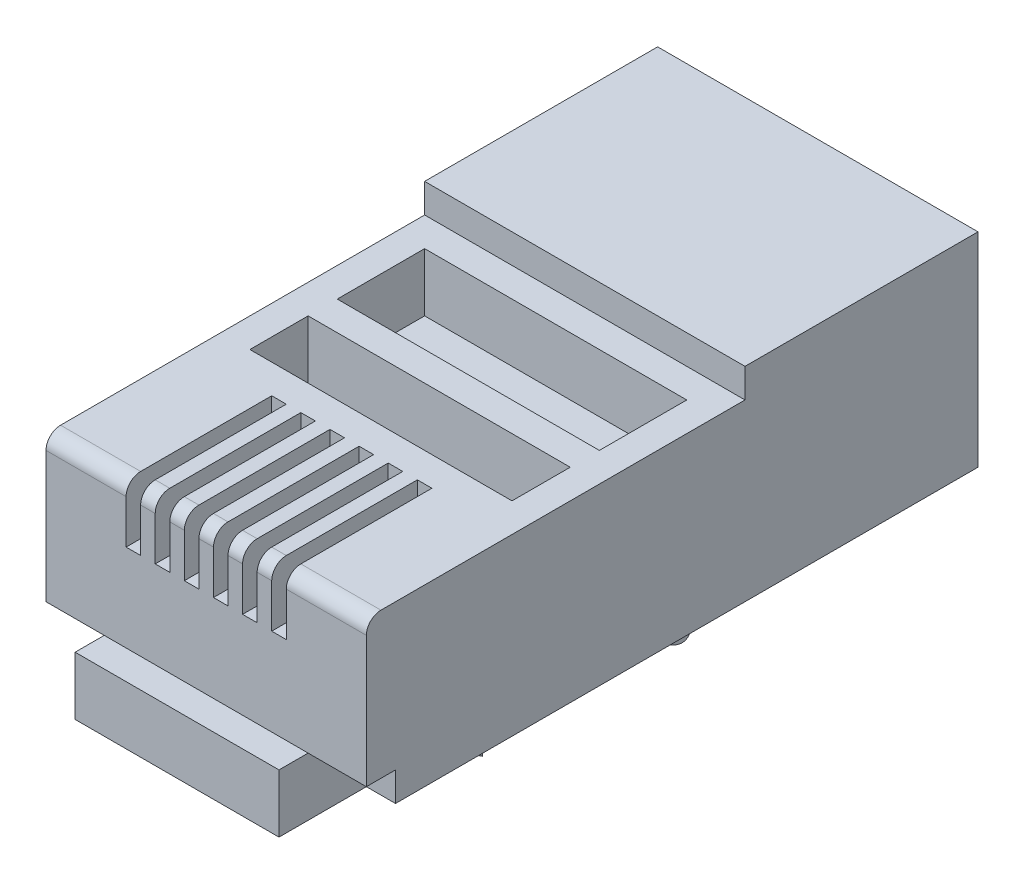
SolidWorks part; units mm, degrees
ref_plane "Ön Düzlem" through (0, 0, 0) normal (0, 0, 1) x (1, 0, 0)
ref_plane "Üst Düzlem" through (0, 0, 0) normal (0, 1, 0) x (1, 0, 0)
ref_plane "Sağ Düzlem" through (0, 0, 0) normal (1, 0, 0) x (0, 0, -1)
sketch "Sketch1" plane through (0, 0, 0) normal (0, 0, 1) x (1, 0, 0)
  line L0 (-58.5749, 4) -> (-58.5749, 6)
  line L1 (-61.8249, 6) -> (-59.0749, 6)
  line L2 (-61.8249, 6) -> (-61.8249, 0)
  line L3 (-61.8249, 0) -> (-50.8249, 0)
  line L4 (-50.8249, 6) -> (-50.8249, 0)
  line L5 (-58.5749, 6) -> (-58.0749, 6)
  line L6 (-59.0749, 6) -> (-59.0749, 4)
  line L7 (-59.0749, 4) -> (-58.5749, 4)
  line L8 (-53.5749, 6) -> (-53.5749, 4)
  line L9 (-58.0749, 4) -> (-58.0749, 6)
  line L10 (-57.5749, 4) -> (-57.5749, 6)
  line L11 (-57.0749, 6) -> (-57.0749, 4)
  line L12 (-56.5749, 6) -> (-56.5749, 4)
  line L13 (-56.0749, 6) -> (-56.0749, 4)
  line L14 (-58.5749, 6) -> (-58.0749, 6)
  line L15 (-57.5749, 6) -> (-57.0749, 6)
  line L16 (-57.5749, 6) -> (-57.0749, 6)
  line L17 (-56.5749, 6) -> (-56.0749, 6)
  line L18 (-56.5749, 6) -> (-56.0749, 6)
  line L19 (-58.0749, 4) -> (-57.5749, 4)
  line L20 (-57.0749, 4) -> (-56.5749, 4)
  line L21 (-56.0749, 4) -> (-55.5749, 4)
  line L22 (-55.5749, 4) -> (-55.5749, 6)
  line L23 (-55.0749, 6) -> (-55.0749, 4)
  line L24 (-55.0749, 4) -> (-54.5749, 4)
  line L25 (-54.5749, 6) -> (-54.5749, 4)
  line L26 (-55.5749, 6) -> (-55.0749, 6)
  line L27 (-55.5749, 6) -> (-55.0749, 6)
  line L28 (-54.5749, 6) -> (-54.0749, 6)
  line L29 (-54.5749, 6) -> (-54.0749, 6)
  line L30 (-54.0749, 4) -> (-54.0749, 6)
  line L31 (-54.0749, 4) -> (-53.5749, 4)
  line L32 (-53.5749, 6) -> (-50.8249, 6)
  dimension "D1" = 6
  dimension "D2" = 11
  dimension "D3" = 2.75
  dimension "D4" = 0.5
  dimension "D5" = 0.5
  dimension "D6" = 0.5
  dimension "D7" = 0.5
  dimension "D8" = 0.5
  dimension "D9" = 0.5
  dimension "D10" = 0.5
  dimension "D11" = 0.5
  dimension "D12" = 0.5
  dimension "D13" = 0.5
  dimension "D14" = 0.5
  dimension "D15" = 2
extrude "Boss-Extrude1" add sketch "Sketch1" against normal blind 5 contours L32 L8 L31 L30 L28 L25 L24 L23 L26 L22 L21 L13 L17 L12 L20 L11 L15 L10 L19 L9 L5 L0 L7 L6 L1 L2 L3 L4
sketch "Sketch2" plane through (0, 0, -5) normal (0, 0, -1) x (-1, 0, 0)
  line L1 (50.8249, 6) -> (61.8249, 6)
  line L2 (50.8249, 6) -> (50.8249, 0)
  line L3 (50.8249, 0) -> (61.8249, 0)
  line L4 (61.8249, 6) -> (61.8249, 0)
extrude "Boss-Extrude2" add sketch "Sketch2" along normal blind 8
sketch "Sketch3" plane through (0, 6, 0) normal (0, 1, 0) x (1, 0, 0)
  line L0 (-56.0749, 5) -> (-55.5749, 5) construction
  line L1 (-60.8249, 6) -> (-51.8249, 6)
  line L2 (-60.8249, 6) -> (-60.8249, 8)
  line L3 (-60.8249, 8) -> (-51.8249, 8)
  line L4 (-51.8249, 6) -> (-51.8249, 8)
  line L5 (-50.8249, 13) -> (-50.8249, 0) construction
  line L6 (-61.8249, 13) -> (-61.8249, 0) construction
  dimension "D1" = 1
  dimension "D2" = 1
  dimension "D3" = 1
  dimension "D4" = 2
extrude "Cut-Extrude1" cut sketch "Sketch3" against normal blind 2
sketch "Sketch5" plane through (0, 6, 0) normal (0, 1, 0) x (1, 0, 0)
  line L0 (-51.8249, 8) -> (-60.8249, 8) construction
  line L1 (-60.8249, 9) -> (-51.8249, 9)
  line L2 (-60.8249, 9) -> (-60.8249, 12)
  line L3 (-60.8249, 12) -> (-51.8249, 12)
  line L4 (-51.8249, 12) -> (-51.8249, 9)
  line L5 (-61.8249, 13) -> (-61.8249, 0) construction
  line L8 (-50.8249, 13) -> (-50.8249, 0) construction
  line L9 (-61.8249, 13) -> (-50.8249, 13) construction
  dimension "D1" = 1
  dimension "D2" = 1
  dimension "D3" = 1
  dimension "D4" = 1
extrude "Cut-Extrude2" cut sketch "Sketch5" against normal blind 2
sketch "Sketch7" plane through (0, 0, -13) normal (0, 0, -1) x (-1, 0, 0)
  line L1 (50.8249, 0) -> (61.8249, 0)
  line L2 (50.8249, 0) -> (50.8249, 7)
  line L3 (50.8249, 7) -> (61.8249, 7)
  line L4 (61.8249, 0) -> (61.8249, 7)
  line L5 (61.8249, 6) -> (50.8249, 6) construction
  dimension "D1" = 1
extrude "Boss-Extrude3" add sketch "Sketch7" along normal blind 8
sketch "Sketch8" plane through (0, 0, 0) normal (0, 0, 1) x (1, 0, 0)
  line L0 (-61.8249, 6) -> (-61.8249, 0) construction
  line L1 (-59.8249, 1) -> (-52.8249, 1)
  line L2 (-59.8249, 1) -> (-59.8249, -1)
  line L3 (-59.8249, -1) -> (-52.8249, -1)
  line L4 (-52.8249, 1) -> (-52.8249, -1)
  line L5 (-50.8249, 6) -> (-50.8249, 0) construction
  line L6 (-61.8249, 0) -> (-50.8249, 0) construction
  dimension "D1" = 2
  dimension "D2" = 2
  dimension "D3" = 1
  dimension "D4" = 1
extrude "Boss-Extrude4" add sketch "Sketch8" along normal blind 1
sketch "Sketch9" plane through (0, 0, 0) normal (0, 0, 1) x (1, 0, 0)
  line L0 (-52.8249, 0) -> (-52.8249, 1) construction
  line L1 (-59.8249, 1) -> (-61.8249, 1)
  line L2 (-59.8249, 1) -> (-59.8249, 0)
  line L3 (-59.8249, 0) -> (-61.8249, 0)
  line L4 (-61.8249, 1) -> (-61.8249, 0)
  line L5 (-50.8249, 0) -> (-52.8249, 0)
  line L6 (-50.8249, 0) -> (-50.8249, 1)
  line L7 (-50.8249, 1) -> (-52.8249, 1)
  line L8 (-52.8249, 0) -> (-52.8249, 1)
extrude "Cut-Extrude3" cut sketch "Sketch9" against normal blind 1
sketch "Sketch10" plane through (0, 0, 0) normal (0, -1, 0) x (1, 0, 0)
  line L1 (-59.8249, 0) -> (-52.8249, 0)
  line L2 (-59.8249, 0) -> (-59.8249, -3)
  line L3 (-59.8249, -3) -> (-52.8249, -3)
  line L4 (-52.8249, 0) -> (-52.8249, -3)
  dimension "D1" = 3
extrude "Boss-Extrude5" add sketch "Sketch10" along normal blind 1
sketch "Sketch12" plane through (-52.8249, 0, 0) normal (1, 0, 0) x (0, 0, -1)
  line L0 (3, 0) -> (5.9924, -0.4844)
  line L1 (5.9924, -0.4844) -> (5.9924, -2.0955)
  line L2 (5.9924, -2.0955) -> (4.8965, -1.3396)
  line L3 (4.8965, -1.3396) -> (3, -1)
  line L4 (3, -1) -> (3, 0)
extrude "Boss-Extrude6" add sketch "Sketch12" against normal blind 7
ref_plane "Plane2" through (-53.8249, 0, 0) normal (1, 0, 0) x (0, 0, -1)
sketch "Sketch13" plane through (-53.8249, 0, 0) normal (1, 0, 0) x (0, 0, -1)
  line L0 (14.149, -2.4619) -> (14.149, -2.8398)
  line L1 (5.9924, -2.0955) -> (5.9924, -0.4844)
  arc A0 (14.149, -2.4619) -> (13.9439, -2.1773) centre (13.849, -2.4619) ccw
  arc A1 (13.8795, -3.1383) -> (14.149, -2.8398) centre (13.849, -2.8398) ccw
  spline S0 degree 3 poles (5.9924, -0.4844) (8.7077, -0.7502) (11.3599, -1.3149) (13.9439, -2.1773) knots 0 0 0 0 0.957735 0.957735 0.957735 0.957735
  spline S1 degree 3 poles (5.9924, -2.0955) (8.2912, -2.4166) (10.9326, -1.9089) (13.4495, -2.9904) (13.6965, -3.157) (13.8795, -3.1383) knots 0 0 0 0 0.841667 0.882834 0.948247 0.948247 0.948247 0.948247
  dimension "D1" = 0.3
  dimension "D2" = 0.3
extrude "Boss-Extrude7" add sketch "Sketch13" against normal blind 5
sketch "Sketch14" plane through (0, 4, 0) normal (0, 1, 0) x (1, 0, 0)
  line L0 (-53.5749, 5) -> (-53.5749, 0) construction
  line L1 (-53.5749, 1.5) -> (-54.0749, 1.5)
  line L2 (-53.5749, 1.5) -> (-53.5749, 3.5)
  line L3 (-53.5749, 3.5) -> (-54.0749, 3.5)
  line L4 (-54.0749, 1.5) -> (-54.0749, 3.5)
  line L5 (-54.0749, 5) -> (-54.0749, 0) construction
  line L6 (-54.0749, 0) -> (-53.5749, 0) construction
  line L8 (-54.5749, 1.5) -> (-55.0749, 1.5)
  line L9 (-54.5749, 1.5) -> (-54.5749, 3.5)
  line L10 (-54.5749, 3.5) -> (-55.0749, 3.5)
  line L11 (-55.0749, 1.5) -> (-55.0749, 3.5)
  line L12 (-55.5749, 1.5) -> (-56.0749, 1.5)
  line L13 (-55.5749, 1.5) -> (-55.5749, 3.5)
  line L14 (-55.5749, 3.5) -> (-56.0749, 3.5)
  line L15 (-56.0749, 1.5) -> (-56.0749, 3.5)
  line L16 (-56.5749, 1.5) -> (-57.0749, 1.5)
  line L17 (-56.5749, 1.5) -> (-56.5749, 3.5)
  line L18 (-56.5749, 3.5) -> (-57.0749, 3.5)
  line L19 (-57.0749, 1.5) -> (-57.0749, 3.5)
  line L20 (-57.5749, 1.5) -> (-58.0749, 1.5)
  line L21 (-57.5749, 1.5) -> (-57.5749, 3.5)
  line L22 (-57.5749, 3.5) -> (-58.0749, 3.5)
  line L23 (-58.0749, 1.5) -> (-58.0749, 3.5)
  line L24 (-58.5749, 1.5) -> (-59.0749, 1.5)
  line L25 (-58.5749, 1.5) -> (-58.5749, 3.5)
  line L26 (-58.5749, 3.5) -> (-59.0749, 3.5)
  line L27 (-59.0749, 1.5) -> (-59.0749, 3.5)
  point P8 (-53.8249, 0)
  dimension "D1" = 1.5
  dimension "D2" = 2
  dimension "D3" = 6
extrude "Cut-Extrude4" cut sketch "Sketch14" against normal blind 1
sketch "Sketch15" plane through (0, 0, -21) normal (0, 0, -1) x (-1, 0, 0)
  line L0 (61.8249, 7) -> (50.8249, 7) construction
  line L1 (52.8249, 5) -> (59.8249, 5)
  line L2 (52.8249, 5) -> (52.8249, 2)
  line L3 (52.8249, 2) -> (59.8249, 2)
  line L4 (59.8249, 5) -> (59.8249, 2)
  line L5 (50.8249, 7) -> (50.8249, 0) construction
  line L6 (61.8249, 0) -> (61.8249, 7) construction
  line L7 (50.8249, 0) -> (61.8249, 0) construction
  dimension "D1" = 2
  dimension "D2" = 2
  dimension "D3" = 2
  dimension "D4" = 2
extrude "Cut-Extrude5" cut sketch "Sketch15" against normal blind 8
sketch "Sketch16" plane through (0, 0, -13) normal (0, 0, -1) x (-1, 0, 0)
  line L0 (54.0749, 3) -> (54.0749, 4) construction
  line L7 (52.8249, 2) -> (59.8249, 2) construction
  circle A0 centre (53.8249, 3.25) radius 0.25
  circle A1 centre (54.8249, 3.25) radius 0.25
  circle A2 centre (55.8249, 3.25) radius 0.25
  circle A3 centre (56.8249, 3.25) radius 0.25
  circle A4 centre (57.8249, 3.25) radius 0.25
  circle A5 centre (58.8249, 3.25) radius 0.25
  dimension "D1" = 0.5
  dimension "D2" = 0.25
  dimension "D3" = 1.25
  dimension "D4" = 6
extrude "Cut-Extrude10" cut sketch "Sketch16" against normal blind 10
fillet "Fillet1" radius 0.5 7 edges at (-60.4499, 6, 0) (-58.3249, 6, 0) (-57.3249, 6, 0) (-56.3249, 6, 0) (-55.3249, 6, 0) (-54.3249, 6, 0) (-52.1999, 6, 0)
